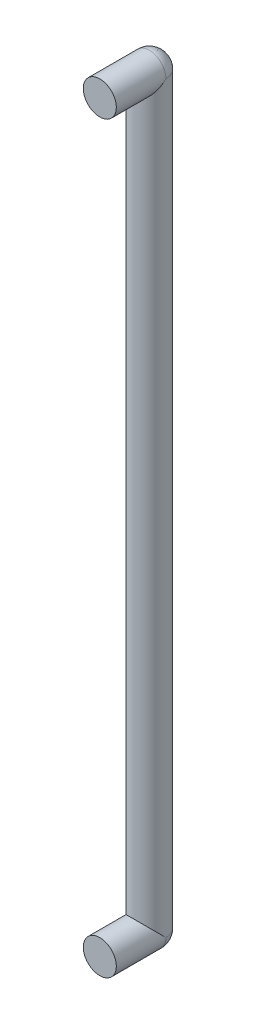
SolidWorks part; units mm, degrees
ref_plane "Front Plane" through (0, 0, 0) normal (0, 0, 1) x (1, 0, 0)
ref_plane "Top Plane" through (0, 0, 0) normal (0, 1, 0) x (1, 0, 0)
ref_plane "Right Plane" through (0, 0, 0) normal (1, 0, 0) x (0, 0, -1)
sketch "Sketch1" plane through (0, 0, 0) normal (0, 1, 0) x (1, 0, 0)
  circle A0 centre (0, 0) radius 0.1
  dimension "D1" = 0.2
extrude "Boss-Extrude1" add sketch "Sketch1" along normal blind 4.5
sketch "Sketch2" plane through (0, 0, 0) normal (0, 0, 1) x (1, 0, 0)
  line L0 (0.1, 4.5) -> (-0.1, 4.5) construction
  circle A0 centre (0, 4.5) radius 0.1
  circle A1 centre (0, 0) radius 0.1
extrude "Boss-Extrude2" add sketch "Sketch2" along normal blind 0.3
sketch "Sketch5" plane through (0, 0, 0) normal (0, 0, -1) x (-1, 0, 0)
  line L0 (-0.1, 4.5) -> (0.1, 4.5)
  arc A0 (0.1, 4.5) -> (-0.1, 4.5) centre (0, 4.5) ccw
revolve "Revolve1" add sketch "Sketch5" angle 90 about L0
sketch "Sketch6" plane through (0, 0, 0) normal (0, 0, -1) x (-1, 0, 0)
  line L0 (-0.1, 0) -> (0.1, 0)
  arc A0 (-0.1, 0) -> (0.1, 0) centre (0, 0) ccw
revolve "Revolve2" add sketch "Sketch6" angle 90 about L0
